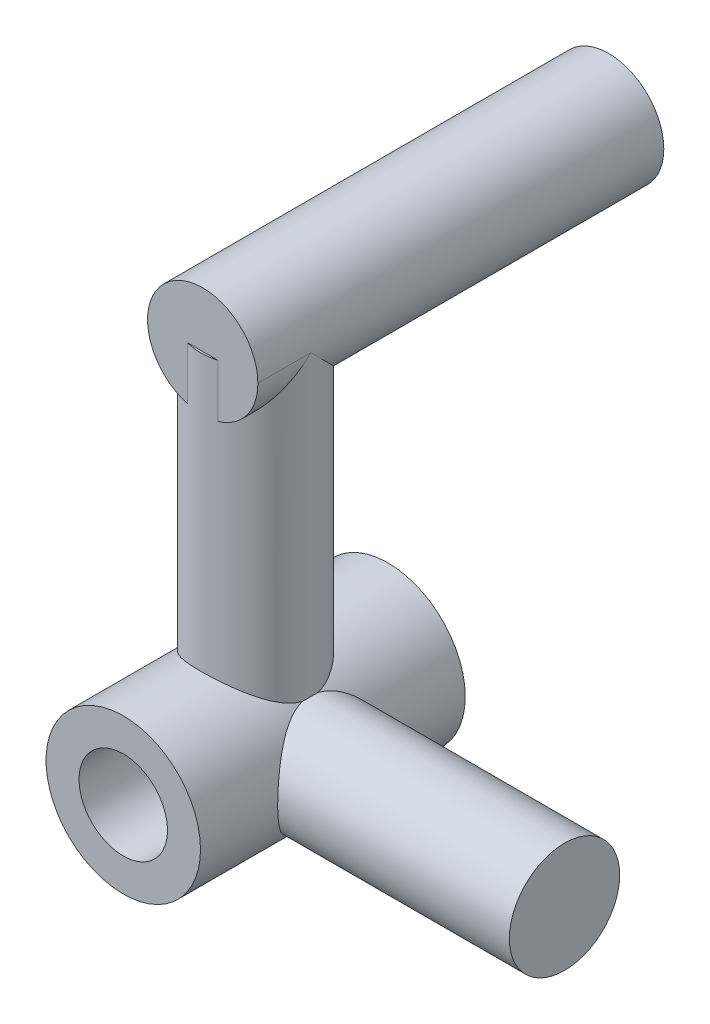
SolidWorks part; units mm, degrees
ref_plane "Front Plane" through (0, 0, 0) normal (0, 0, 1) x (1, 0, 0)
ref_plane "Top Plane" through (0, 0, 0) normal (0, 1, 0) x (1, 0, 0)
ref_plane "Right Plane" through (0, 0, 0) normal (1, 0, 0) x (0, 0, -1)
sketch "Sketch1" plane through (0, 0, 0) normal (0, 0, 1) x (1, 0, 0)
  circle A0 centre (0, 0) radius 1.75
  circle A2 centre (0, 0) radius 1
  dimension "D1" = 2
  dimension "D2" = 3.5
extrude "Boss-Extrude1" add sketch "Sketch1" against normal mid plane 6
sketch "Sketch4" plane through (0, 0, 0) normal (1, 0, 0) x (0, 0, -1)
  circle A0 centre (0, 0) radius 1.25
  dimension "D1" = 2.5
extrude "Boss-Extrude2" add sketch "Sketch4" along normal blind 7
sketch "Sketch5" plane through (0, 0, 3) normal (0, 0, 1) x (1, 0, 0)
  circle A0 centre (0, 0) radius 1.0023
extrude "Cut-Extrude1" cut sketch "Sketch5" against normal through all
sketch "Sketch6" plane through (0, 0, 0) normal (0, 1, 0) x (1, 0, 0)
  circle A0 centre (0, 0) radius 1.25
  dimension "D1" = 2.5
extrude "Boss-Extrude3" add sketch "Sketch6" along normal blind 8
sketch "Sketch7" plane through (0, 0, 0) normal (0, 0, 1) x (1, 0, 0)
  line L0 (1.25, 8) -> (-1.25, 8) construction
  circle A0 centre (0, 8) radius 1.25
extrude "Boss-Extrude4" add sketch "Sketch7" against normal blind 8
sketch "Sketch8" plane through (0, 0, 0) normal (0, 0, 1) x (1, 0, 0)
  line L0 (1.25, 8) -> (-1.25, 8) construction
  circle A0 centre (0, 8) radius 1.25
extrude "Boss-Extrude5" add sketch "Sketch8" along normal blind 1.2
